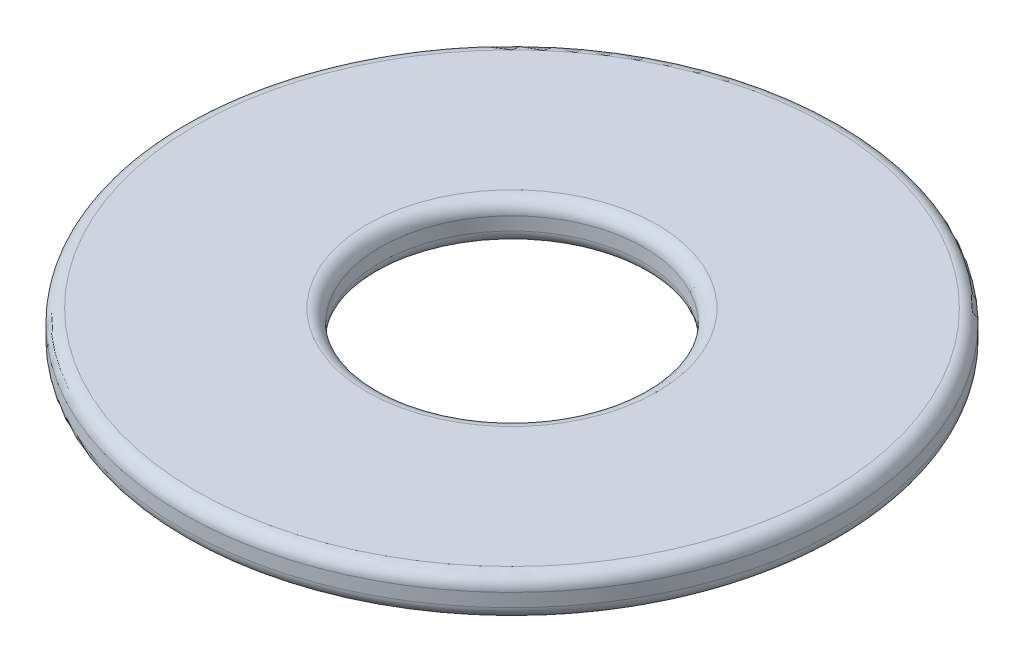
SolidWorks part; units mm, degrees
material "Cast Carbon Steel"
ref_plane "Front Plane" through (0, 0, 0) normal (0, 0, 1) x (1, 0, 0)
ref_plane "Top Plane" through (0, 0, 0) normal (0, 1, 0) x (1, 0, 0)
ref_plane "Right Plane" through (0, 0, 0) normal (1, 0, 0) x (0, 0, -1)
sketch "Sketch1" plane through (0, 0, 0) normal (0, 1, 0) x (1, 0, 0)
  circle A0 centre (0, 0) radius 10
  circle A1 centre (0, 0) radius 4
  dimension "D1" = 8
  dimension "D2" = 20
extrude "Boss-Extrude1" add sketch "Sketch1" along normal blind 1.2
fillet "Fillet1" radius 0.4 4 edges at (0, 0, 10) (0, 1.2, 10) (0, 0, 4) (0, 1.2, 4)
